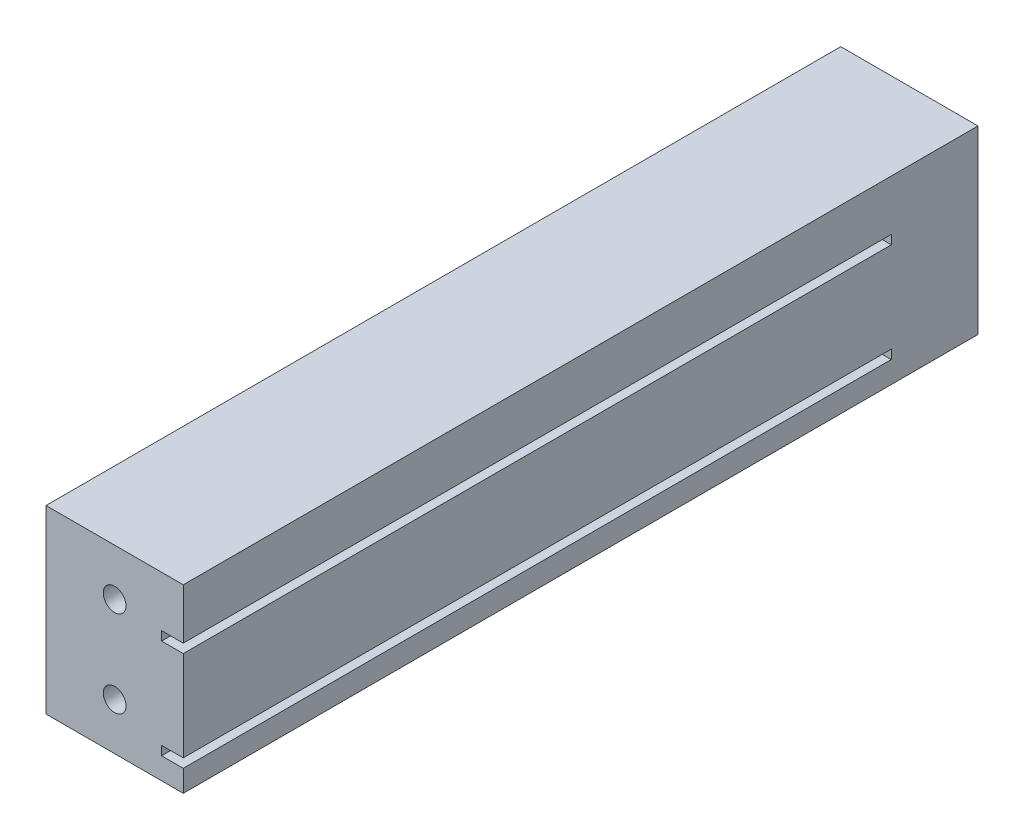
SolidWorks part; units mm, degrees
ref_plane "Ebene vorne" through (0, 0, 0) normal (0, 0, 1) x (1, 0, 0)
ref_plane "Ebene oben" through (0, 0, 0) normal (0, 1, 0) x (1, 0, 0)
ref_plane "Ebene rechts" through (0, 0, 0) normal (1, 0, 0) x (0, 0, -1)
sketch "Sketch1" plane through (0, 0, 0) normal (0, 1, 0) x (1, 0, 0)
  line L1 (9.5, -55) -> (-9.5, -55)
  line L2 (9.5, -55) -> (9.5, 55)
  line L3 (9.5, 55) -> (-9.5, 55)
  line L4 (-9.5, -55) -> (-9.5, 55)
  line L5 (9.5, -55) -> (-9.5, 55) construction
  line L6 (9.5, 55) -> (-9.5, -55) construction
  point P0 (0, 0)
  dimension "D1" = 19
  dimension "D2" = 110
extrude "Block" add sketch "Sketch1" along normal blind 25
sketch "Sketch2" plane through (9.5, 0, 0) normal (1, 0, 0) x (0, 0, -1)
  line L0 (-55, 25) -> (-55, 0) construction
  line L1 (-55, 4.25) -> (43, 4.25)
  line L2 (-55, 4.25) -> (-55, 3)
  line L3 (-55, 3) -> (43, 3)
  line L4 (43, 4.25) -> (43, 3)
  line L5 (-55, 25) -> (55, 25) construction
  line L6 (-55, 0) -> (55, 0) construction
  line L7 (-55, 18) -> (43, 18)
  line L8 (-55, 18) -> (-55, 16.75)
  line L9 (-55, 16.75) -> (43, 16.75)
  line L10 (43, 18) -> (43, 16.75)
  dimension "D1" = 1.25
  dimension "D2" = 7
  dimension "D3" = 3
  dimension "D4" = 98
extrude "Slides" cut sketch "Sketch2" against normal blind 3
sketch "Sketch3" plane through (-9.5, 0, 0) normal (-1, 0, 0) x (0, 0, 1)
  line L0 (55, 25) -> (55, 0) construction
  line L2 (-55, 0) -> (55, 0) construction
  circle A0 centre (-50, 6) radius 1.5
  circle A1 centre (51, 6) radius 1.5
  dimension "D2" = 3
  dimension "D1" = 101
  dimension "D3" = 4
  dimension "D4" = 6
extrude "Mounting Holes" cut sketch "Sketch3" against normal blind 10
sketch "Sketch5" plane through (0, 0, 55) normal (0, 0, 1) x (1, 0, 0)
  line L0 (0, 25) -> (0, 0) construction
  line L1 (-9.5, 0) -> (9.5, 0) construction
  line L3 (-9.5, 25) -> (9.5, 25) construction
  line L4 (0, 12.5) -> (-5.3784, 12.5) construction
  circle A0 centre (0, 18.5) radius 1.575
  circle A1 centre (0, 6.5) radius 1.575
  dimension "D1" = 3.15
  dimension "D2" = 6
extrude "Cut-Extrude1" cut sketch "Sketch5" against normal blind 15 draft 1
equation "\"PCB\"=98"
equation "\"WithCase\"=101"
equation "\"D4@Sketch2\"=\"PCB\""
